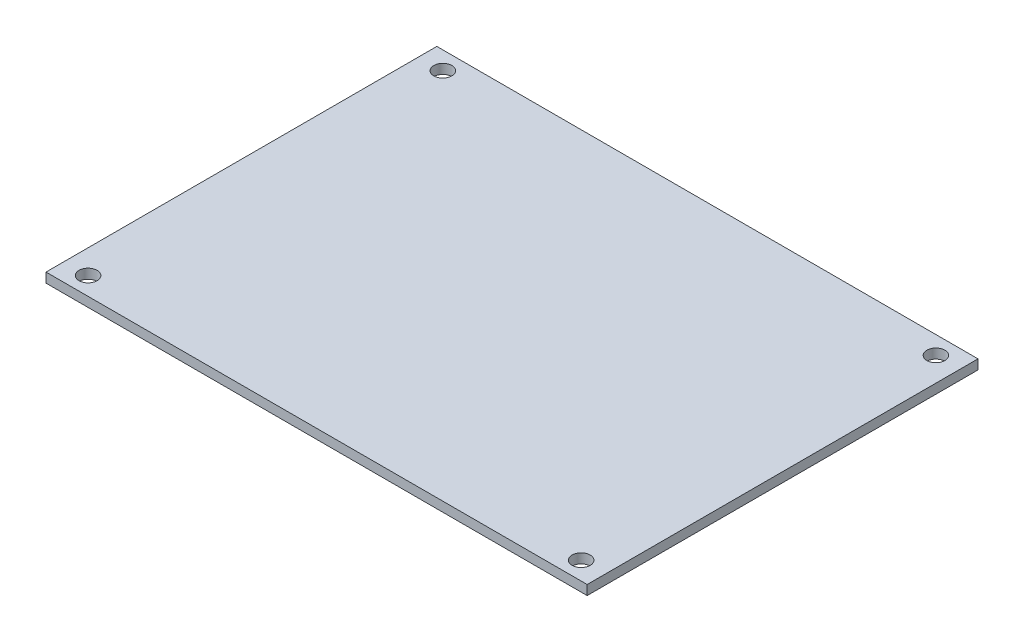
SolidWorks part; units mm, degrees
ref_plane "Front Plane" through (0, 0, 0) normal (0, 0, 1) x (1, 0, 0)
ref_plane "Top Plane" through (0, 0, 0) normal (0, 1, 0) x (1, 0, 0)
ref_plane "Right Plane" through (0, 0, 0) normal (1, 0, 0) x (0, 0, -1)
sketch "Sketch1" plane through (0, 0, 0) normal (0, 1, 0) x (1, 0, 0)
  line L1 (0, 0) -> (90, 0)
  line L2 (0, 0) -> (0, 65)
  line L3 (0, 65) -> (90, 65)
  line L4 (90, 0) -> (90, 65)
  circle A0 centre (4, 3) radius 1.5
  circle A1 centre (86, 3) radius 1.5
  circle A2 centre (4, 62) radius 1.5
  circle A3 centre (86, 62) radius 1.5
  dimension "D4" = 3
  dimension "D8" = 3
  dimension "D9" = 3
  dimension "D10" = 3
  dimension "D1" = 90
  dimension "D2" = 65
  dimension "D3" = 82
  dimension "D5" = 59
  dimension "D6" = 3
  dimension "D7" = 4
extrude "Boss-Extrude1" add sketch "Sketch1" along normal blind 1.6
